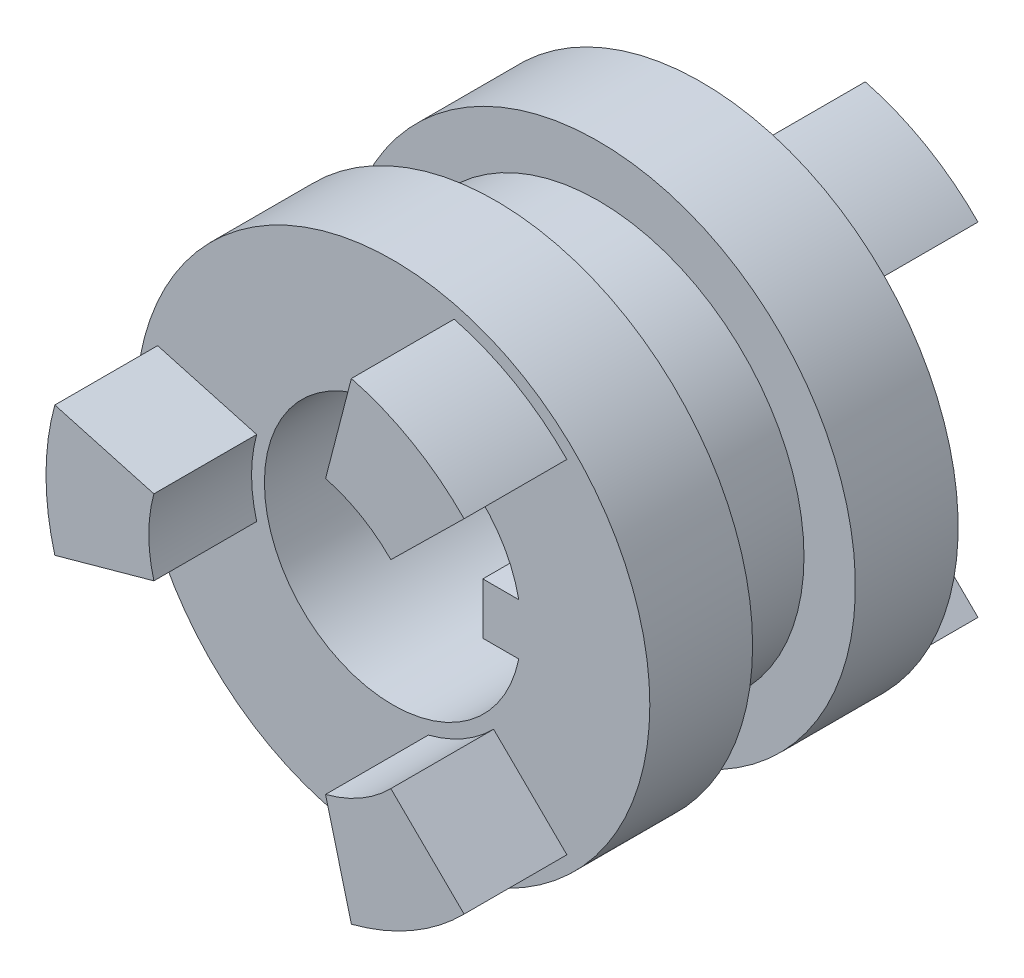
SolidWorks part; units mm, degrees
ref_plane "Front Plane" through (0, 0, 0) normal (0, 0, 1) x (1, 0, 0)
ref_plane "Top Plane" through (0, 0, 0) normal (0, 1, 0) x (1, 0, 0)
ref_plane "Right Plane" through (0, 0, 0) normal (1, 0, 0) x (0, 0, -1)
sketch "Sketch1" plane through (0, 0, 0) normal (0, 0, 1) x (1, 0, 0)
  circle A0 centre (0, 0) radius 10
  circle A1 centre (0, 0) radius 5
  dimension "D1" = 20
  dimension "D2" = 10
extrude "Boss-Extrude2" add sketch "Sketch1" along normal blind 4
sketch "Sketch2" plane through (0, 0, 4) normal (0, 0, 1) x (1, 0, 0)
  line L0 (-10, 0) -> (-9.5, 0)
  line L1 (-5.3008, 1.4667) -> (-9.156, 2.5333)
  line L2 (-5.3008, -1.4667) -> (-9.156, -2.5333)
  line L3 (-5.5, 0) -> (-5, 0)
  line L4 (3.9206, 3.8573) -> (6.7719, 6.6627)
  line L5 (1.3802, 5.324) -> (2.3841, 9.196)
  line L6 (1.3802, -5.324) -> (2.3841, -9.196)
  line L7 (3.9206, -3.8573) -> (6.7719, -6.6627)
  circle A0 centre (0, 0) radius 10 construction
  circle A1 centre (0, 0) radius 5 construction
  circle A3 centre (0, 0) radius 9.5
  circle A4 centre (0, 0) radius 5.5
  point P27 (0, 0)
  dimension "D1" = 3
extrude "Boss-Extrude3" add sketch "Sketch2" along normal blind 4 contours A4 L1 A3 L2 | A4 L6 A3 L7 | A4 L4 A3 L5
ref_plane "Plane1" through (4.578, 7.9293, 0) normal (0.5, 0.866, 0) x (0.866, -0.5, 0)
sketch "Sketch3" plane through (0, 0, 0) normal (0, 0, -1) x (-1, 0, 0)
  line L1 (-6.5, 1) -> (-3.5, 1)
  line L2 (-6.5, 1) -> (-6.5, -1)
  line L3 (-6.5, -1) -> (-3.5, -1)
  line L4 (-3.5, 1) -> (-3.5, -1)
  line L5 (-6.5, 1) -> (-3.5, -1) construction
  line L6 (-6.5, -1) -> (-3.5, 1) construction
  circle A0 centre (0, 0) radius 5 construction
  point P0 (-5, 0)
  dimension "D1" = 3
  dimension "D2" = 2
extrude "Boss-Extrude4" add sketch "Sketch3" against normal blind 4
sketch "Sketch4" plane through (0, 0, 0) normal (0, 0, -1) x (-1, 0, 0)
  line L1 (-4.9749, 0.5) -> (-3.5, 0.5)
  line L3 (-4.899, -1) -> (-3.5, -1)
  line L4 (-3.5, 0.5) -> (-3.5, -1)
  circle A0 centre (0, 0) radius 8
  arc A1 (-4.899, -1) -> (-4.9749, 0.5) centre (0, 0) ccw
  point P4 (-5, 0)
  dimension "D1" = 16
extrude "Boss-Extrude5" add sketch "Sketch4" along normal blind 4
sketch "Sketch5" plane through (0, 0, -4) normal (0, 0, -1) x (-1, 0, 0)
  line L1 (-4.9749, 0.5) -> (-3.5, 0.5)
  line L3 (-4.899, -1) -> (-3.5, -1)
  line L4 (-3.5, 0.5) -> (-3.5, -1)
  circle A0 centre (0, 0) radius 10
  arc A1 (-4.899, -1) -> (-4.9749, 0.5) centre (0, 0) ccw
  point P4 (-5, 0)
extrude "Boss-Extrude6" add sketch "Sketch5" along normal blind 4
sketch "Sketch6" plane through (0, 0, -8) normal (0, 0, -1) x (-1, 0, 0)
  line L0 (-1.3802, 5.324) -> (-2.3841, 9.196)
  line L1 (-1.3802, 5.324) -> (-2.3841, 9.196) construction
  line L2 (-3.9206, 3.8573) -> (-6.7719, 6.6627)
  line L3 (-3.9206, 3.8573) -> (-6.7719, 6.6627) construction
  line L4 (5.3008, 1.4667) -> (9.156, 2.5333)
  line L5 (5.3008, -1.4667) -> (9.156, -2.5333)
  line L6 (-1.3802, -5.324) -> (-2.3841, -9.196)
  line L7 (-3.9206, -3.8573) -> (-6.7719, -6.6627)
  circle A0 centre (0, 0) radius 9.5
  circle A1 centre (0, 0) radius 5.5
  point P24 (0, 0)
  dimension "D1" = 3
extrude "Boss-Extrude7" add sketch "Sketch6" along normal blind 4 contours A1 L0 A0 L2 | A1 L7 A0 L6 | A1 L5 A0 L4
sketch "Sketch10" plane through (0, 0, -8) normal (0, 0, -1) x (-1, 0, 0)
  line L1 (-6.5, 1) -> (-3.5, 1)
  line L2 (-6.5, 1) -> (-6.5, -1)
  line L3 (-6.5, -1) -> (-3.5, -1)
  line L4 (-3.5, 1) -> (-3.5, -1)
  line L5 (-6.5, 1) -> (-3.5, -1) construction
  line L6 (-6.5, -1) -> (-3.5, 1) construction
  circle A0 centre (0, 0) radius 5
  point P3 (-5, 0)
  line M16 (-3.5, 0.5) -> (-4.9749, 0.5)
  arc M17 (-4.9749, 0.5) -> (-4.899, -1) centre (0, 0) cw
extrude "Boss-Extrude8" add sketch "Sketch10" against normal blind 10 contours L4 L1 M17 M16
